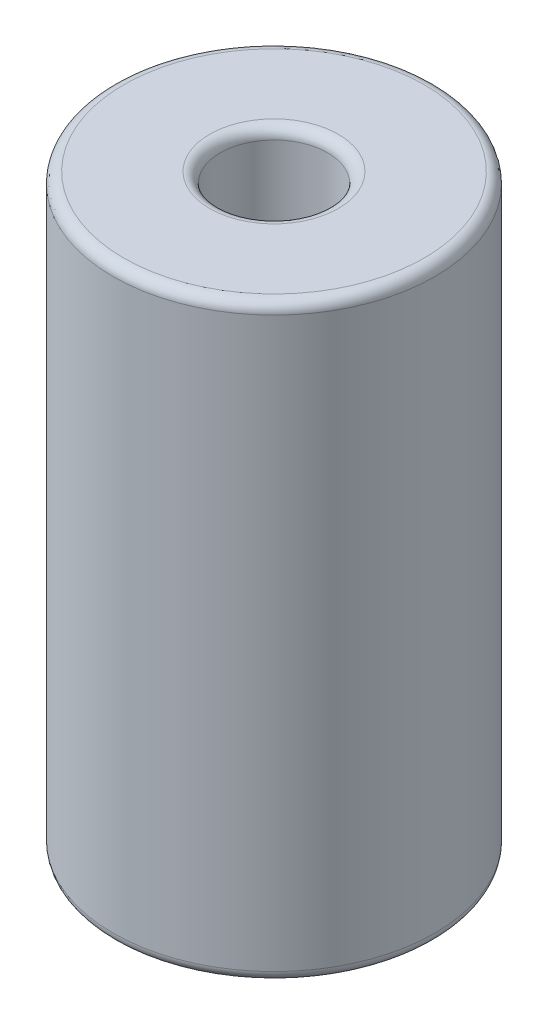
SolidWorks part; units mm, degrees
ref_plane "Front Plane" through (0, 0, 0) normal (0, 0, 1) x (1, 0, 0)
ref_plane "Top Plane" through (0, 0, 0) normal (0, 1, 0) x (1, 0, 0)
ref_plane "Right Plane" through (0, 0, 0) normal (1, 0, 0) x (0, 0, -1)
sketch "Sketch1" plane through (0, 0, 0) normal (0, 1, 0) x (1, 0, 0)
  circle A0 centre (0, 0) radius 3.81
  circle A1 centre (0, 0) radius 1.27
  dimension "D1" = 7.62
  dimension "D2" = 2.54
extrude "Boss-Extrude2" add sketch "Sketch1" along normal blind 13.97
fillet "Fillet1" radius 0.254 4 edges at (0, 13.97, 1.27) (0, 13.97, 3.81) (0, 0, 1.27) (0, 0, 3.81)
